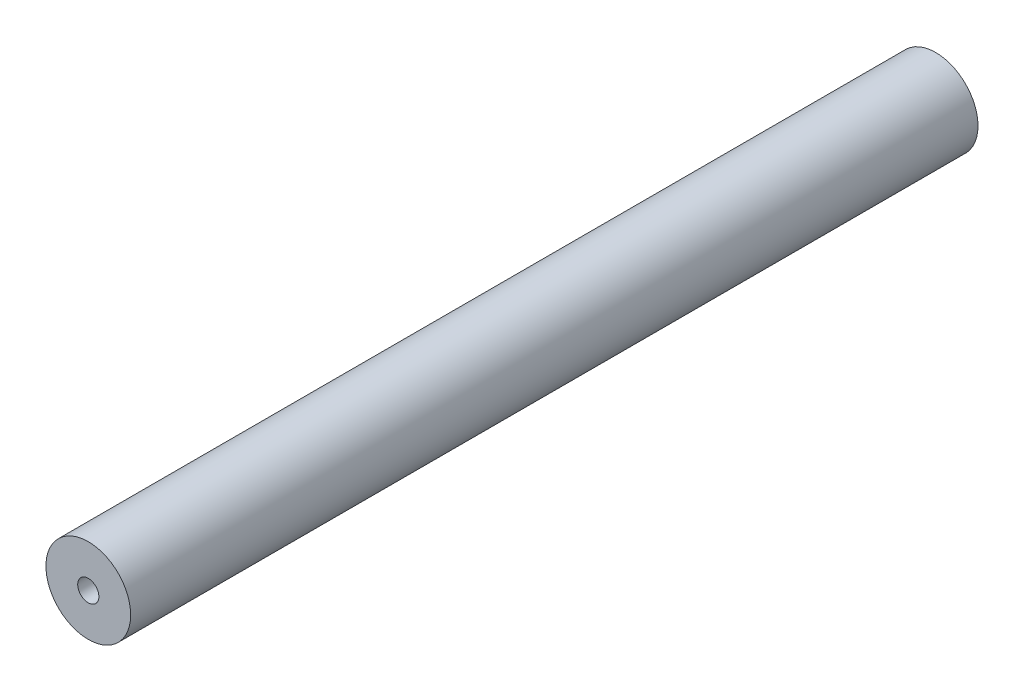
SolidWorks part; units mm, degrees
ref_plane "Front Plane" through (0, 0, 0) normal (0, 0, 1) x (1, 0, 0)
ref_plane "Top Plane" through (0, 0, 0) normal (0, 1, 0) x (1, 0, 0)
ref_plane "Right Plane" through (0, 0, 0) normal (1, 0, 0) x (0, 0, -1)
sketch "Sketch1" plane through (0, 0, 0) normal (0, 0, 1) x (1, 0, 0)
  circle A0 centre (0, 0) radius 25.4
  circle A1 centre (0, 0) radius 6.35
  dimension "D1" = 50.8
  dimension "D2" = 12.7
extrude "Boss-Extrude1" add sketch "Sketch1" along normal blind 508
equation "\"Thick\"= \"in\""
